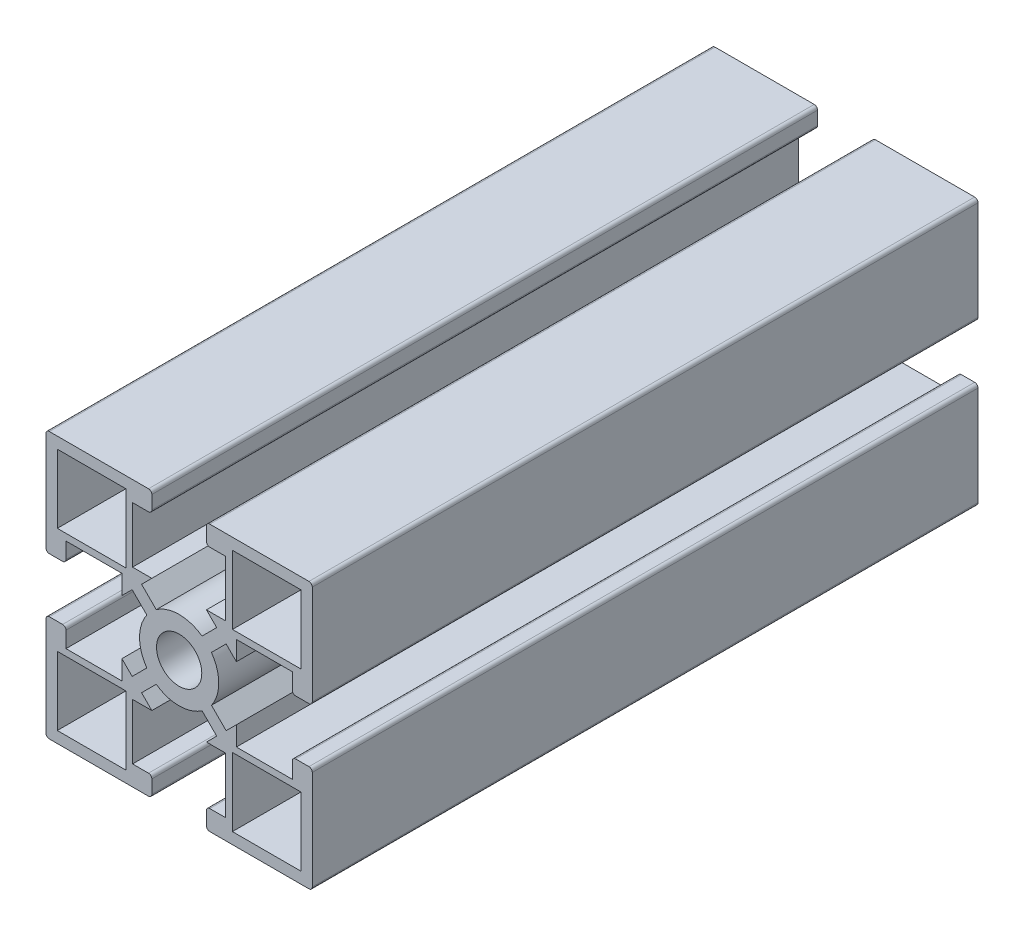
SolidWorks part; units mm, degrees
ref_plane "前视基准面" through (0, 0, 0) normal (0, 0, 1) x (1, 0, 0)
ref_plane "上视基准面" through (0, 0, 0) normal (0, 1, 0) x (1, 0, 0)
ref_plane "右视基准面" through (0, 0, 0) normal (1, 0, 0) x (0, 0, -1)
sketch "草图1" plane through (0, 0, 0) normal (0, 0, 1) x (1, 0, 0)
  line L0 (-8.4828, 18.4514) -> (-18.7828, 18.4514)
  line L1 (-18.7828, 18.4514) -> (-18.7828, 8.1514)
  line L2 (-4.5828, 8.7514) -> (-7.4828, 8.7514)
  line L3 (-17.4828, 7.1514) -> (-17.4828, 4.7514)
  line L4 (-17.9828, 4.2514) -> (-19.9828, 4.2514)
  line L5 (-20.4828, 4.7514) -> (-20.4828, 19.6514)
  line L6 (-19.9828, 20.1514) -> (-5.0828, 20.1514)
  line L7 (-4.5828, 19.6514) -> (-4.5828, 17.6514)
  line L8 (-5.0828, 17.1514) -> (-7.4828, 17.1514)
  line L9 (-9.0828, 7.1514) -> (-9.0828, 4.2514)
  line L10 (-17.4828, 7.1514) -> (-9.0828, 7.1514)
  line L11 (-18.7828, 8.1514) -> (-8.4828, 8.1514)
  line L12 (-7.4828, 17.1514) -> (-7.4828, 8.7514)
  line L13 (-8.4828, 18.4514) -> (-8.4828, 8.1514)
  line L14 (-7.5399, 5.7943) -> (-5.3374, 3.5917)
  line L15 (-6.1257, 7.2085) -> (-3.9231, 5.0059)
  line L16 (-9.0828, 4.2514) -> (-7.5399, 5.7943)
  line L17 (-6.1257, 7.2085) -> (-4.5828, 8.7514)
  line L18 (7.5172, 18.4514) -> (17.8172, 18.4514)
  line L19 (17.8172, 18.4514) -> (17.8172, 8.1514)
  line L20 (3.6172, 8.7514) -> (6.5172, 8.7514)
  line L21 (16.5172, 7.1514) -> (16.5172, 4.7514)
  line L22 (17.0172, 4.2514) -> (19.0172, 4.2514)
  line L23 (19.5172, 4.7514) -> (19.5172, 19.6514)
  line L24 (19.0172, 20.1514) -> (4.1172, 20.1514)
  line L25 (3.6172, 19.6514) -> (3.6172, 17.6514)
  line L26 (4.1172, 17.1514) -> (6.5172, 17.1514)
  line L27 (8.1172, 7.1514) -> (8.1172, 4.2514)
  line L28 (16.5172, 7.1514) -> (8.1172, 7.1514)
  line L29 (17.8172, 8.1514) -> (7.5172, 8.1514)
  line L30 (6.5172, 17.1514) -> (6.5172, 8.7514)
  line L31 (7.5172, 18.4514) -> (7.5172, 8.1514)
  line L32 (6.5743, 5.7943) -> (4.3717, 3.5917)
  line L33 (5.1601, 7.2085) -> (2.9575, 5.0059)
  line L34 (8.1172, 4.2514) -> (6.5743, 5.7943)
  line L35 (5.1601, 7.2085) -> (3.6172, 8.7514)
  line L36 (-8.4828, -18.1486) -> (-18.7828, -18.1486)
  line L37 (-18.7828, -18.1486) -> (-18.7828, -7.8486)
  line L38 (-4.5828, -8.4486) -> (-7.4828, -8.4486)
  line L39 (-17.4828, -6.8486) -> (-17.4828, -4.4486)
  line L40 (-17.9828, -3.9486) -> (-19.9828, -3.9486)
  line L41 (-20.4828, -4.4486) -> (-20.4828, -19.3486)
  line L42 (-19.9828, -19.8486) -> (-5.0828, -19.8486)
  line L43 (-4.5828, -19.3486) -> (-4.5828, -17.3486)
  line L44 (-5.0828, -16.8486) -> (-7.4828, -16.8486)
  line L45 (-9.0828, -6.8486) -> (-9.0828, -3.9486)
  line L46 (-17.4828, -6.8486) -> (-9.0828, -6.8486)
  line L47 (-18.7828, -7.8486) -> (-8.4828, -7.8486)
  line L48 (-7.4828, -16.8486) -> (-7.4828, -8.4486)
  line L49 (-8.4828, -18.1486) -> (-8.4828, -7.8486)
  line L50 (-7.5399, -5.4915) -> (-5.3374, -3.2889)
  line L51 (-6.1257, -6.9057) -> (-3.9231, -4.7031)
  line L52 (-9.0828, -3.9486) -> (-7.5399, -5.4915)
  line L53 (-6.1257, -6.9057) -> (-4.5828, -8.4486)
  line L54 (7.5172, -18.1486) -> (17.8172, -18.1486)
  line L55 (17.8172, -18.1486) -> (17.8172, -7.8486)
  line L56 (3.6172, -8.4486) -> (6.5172, -8.4486)
  line L57 (16.5172, -6.8486) -> (16.5172, -4.4486)
  line L58 (17.0172, -3.9486) -> (19.0172, -3.9486)
  line L59 (19.5172, -4.4486) -> (19.5172, -19.3486)
  line L60 (19.0172, -19.8486) -> (4.1172, -19.8486)
  line L61 (3.6172, -19.3486) -> (3.6172, -17.3486)
  line L62 (4.1172, -16.8486) -> (6.5172, -16.8486)
  line L63 (8.1172, -6.8486) -> (8.1172, -3.9486)
  line L64 (16.5172, -6.8486) -> (8.1172, -6.8486)
  line L65 (17.8172, -7.8486) -> (7.5172, -7.8486)
  line L66 (6.5172, -16.8486) -> (6.5172, -8.4486)
  line L67 (7.5172, -18.1486) -> (7.5172, -7.8486)
  line L68 (6.5743, -5.4915) -> (4.3717, -3.2889)
  line L69 (5.1601, -6.9057) -> (2.9575, -4.7031)
  line L70 (8.1172, -3.9486) -> (6.5743, -5.4915)
  line L71 (5.1601, -6.9057) -> (3.6172, -8.4486)
  arc A0 (-17.9828, 4.2514) -> (-17.4828, 4.7514) centre (-17.9828, 4.7514) ccw
  arc A1 (-20.4828, 4.7514) -> (-19.9828, 4.2514) centre (-19.9828, 4.7514) ccw
  arc A2 (-19.9828, 20.1514) -> (-20.4828, 19.6514) centre (-19.9828, 19.6514) ccw
  arc A3 (-4.5828, 19.6514) -> (-5.0828, 20.1514) centre (-5.0828, 19.6514) ccw
  arc A4 (-5.0828, 17.1514) -> (-4.5828, 17.6514) centre (-5.0828, 17.6514) ccw
  arc A6 (-5.3374, 3.5917) -> (-5.3374, -3.2889) centre (-0.4828, 0.1514) ccw
  arc A7 (-3.9231, -4.7031) -> (2.9575, -4.7031) centre (-0.4828, 0.1514) ccw
  arc A8 (4.3717, -3.2889) -> (4.3717, 3.5917) centre (-0.4828, 0.1514) ccw
  arc A9 (2.9575, 5.0059) -> (-3.9231, 5.0059) centre (-0.4828, 0.1514) ccw
  circle A10 centre (-0.4828, 0.1514) radius 3.4
  arc A11 (16.5172, 4.7514) -> (17.0172, 4.2514) centre (17.0172, 4.7514) ccw
  arc A12 (19.0172, 4.2514) -> (19.5172, 4.7514) centre (19.0172, 4.7514) ccw
  arc A13 (19.5172, 19.6514) -> (19.0172, 20.1514) centre (19.0172, 19.6514) ccw
  arc A14 (4.1172, 20.1514) -> (3.6172, 19.6514) centre (4.1172, 19.6514) ccw
  arc A15 (3.6172, 17.6514) -> (4.1172, 17.1514) centre (4.1172, 17.6514) ccw
  arc A16 (-17.4828, -4.4486) -> (-17.9828, -3.9486) centre (-17.9828, -4.4486) ccw
  arc A17 (-19.9828, -3.9486) -> (-20.4828, -4.4486) centre (-19.9828, -4.4486) ccw
  arc A18 (-20.4828, -19.3486) -> (-19.9828, -19.8486) centre (-19.9828, -19.3486) ccw
  arc A19 (-5.0828, -19.8486) -> (-4.5828, -19.3486) centre (-5.0828, -19.3486) ccw
  arc A20 (-4.5828, -17.3486) -> (-5.0828, -16.8486) centre (-5.0828, -17.3486) ccw
  arc A21 (17.0172, -3.9486) -> (16.5172, -4.4486) centre (17.0172, -4.4486) ccw
  arc A22 (19.5172, -4.4486) -> (19.0172, -3.9486) centre (19.0172, -4.4486) ccw
  arc A23 (19.0172, -19.8486) -> (19.5172, -19.3486) centre (19.0172, -19.3486) ccw
  arc A24 (3.6172, -19.3486) -> (4.1172, -19.8486) centre (4.1172, -19.3486) ccw
  arc A25 (4.1172, -16.8486) -> (3.6172, -17.3486) centre (4.1172, -17.3486) ccw
extrude "凸台-拉伸1" add sketch "草图1" along normal blind 100
